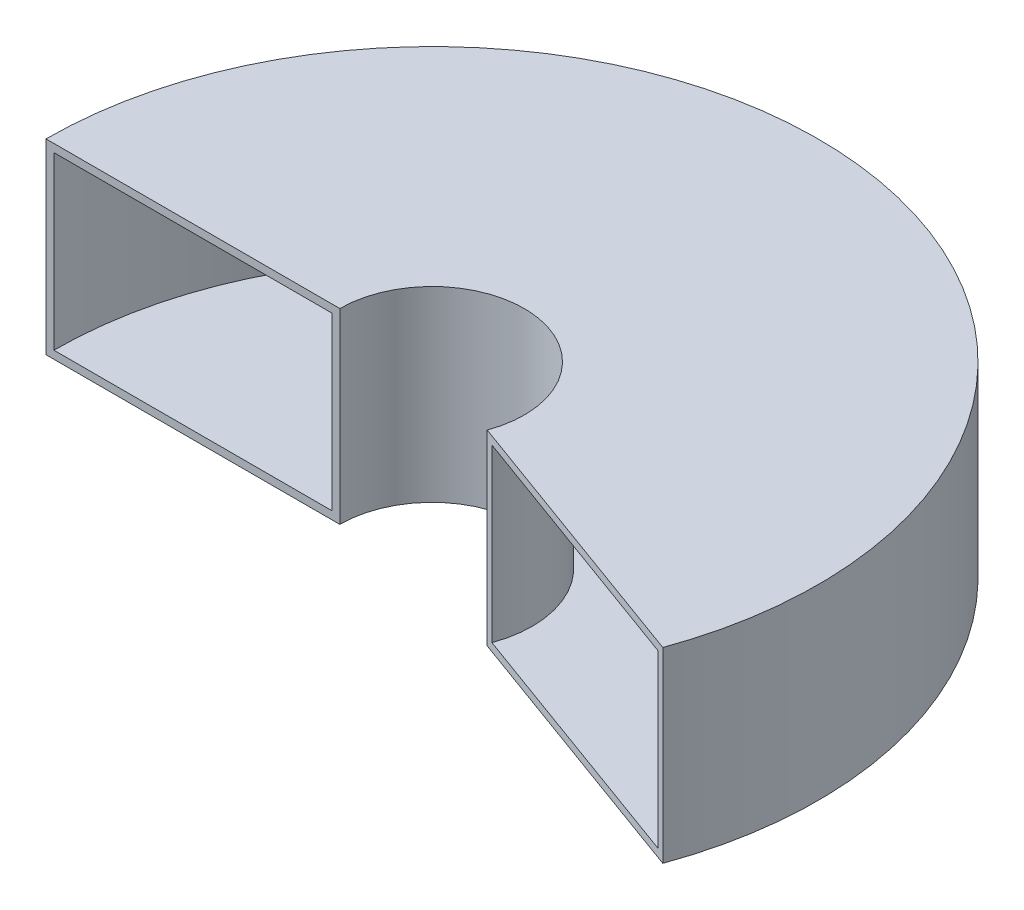
SolidWorks part; units mm, degrees
ref_plane "Front Plane" through (0, 0, 0) normal (0, 0, 1) x (1, 0, 0)
ref_plane "Top Plane" through (0, 0, 0) normal (0, 1, 0) x (1, 0, 0)
ref_plane "Right Plane" through (0, 0, 0) normal (1, 0, 0) x (0, 0, -1)
sketch "Sketch2" plane through (0, 0, 0) normal (0, 0, 1) x (1, 0, 0)
  line L0 (42.0529, 43.794) -> (42.0529, -15.6694)
  line L1 (-79.2845, 39.2405) -> (9.9106, 39.2405)
  line L2 (-79.2845, 39.2405) -> (-79.2845, -15.6694)
  line L3 (-79.2845, -15.6694) -> (9.9106, -15.6694)
  line L4 (9.9106, 39.2405) -> (9.9106, -15.6694)
revolve "Revolve-Thin1" add sketch "Sketch2" angle 200 about L0
